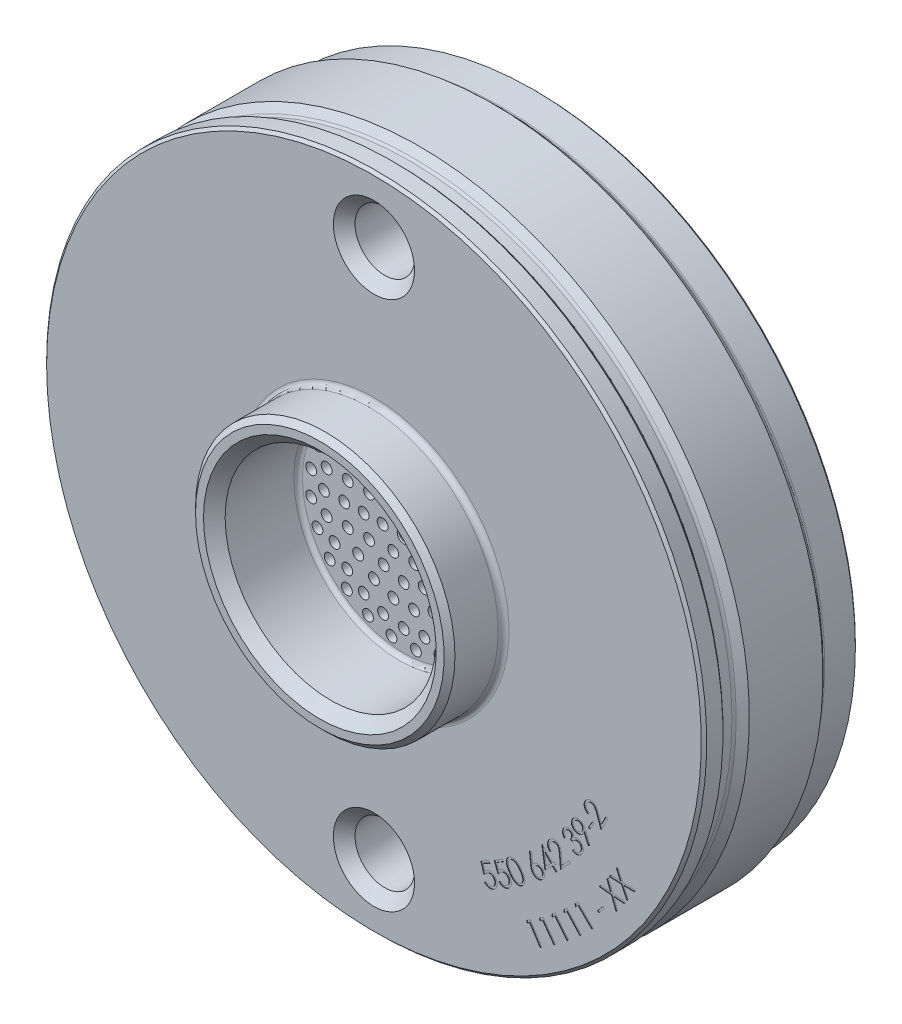
SolidWorks part; units mm, degrees
material "4140 H-T"
ref_plane "Front Plane" through (0, 0, 0) normal (0, 0, 1) x (1, 0, 0)
ref_plane "Top Plane" through (0, 0, 0) normal (0, 1, 0) x (1, 0, 0)
ref_plane "Right Plane" through (0, 0, 0) normal (1, 0, 0) x (0, 0, -1)
sketch "Sketch1" plane through (0, 0, 0) normal (1, 0, 0) x (0, 0, -1)
  line L0 (0, 48.5) -> (0, 59)
  line L1 (-0.5, 59.5) -> (-6.1686, 59.5)
  line L2 (-23.3314, 59.5) -> (-25.18, 59.5)
  line L3 (-39.98, 21.5) -> (-37.98, 19.5)
  line L4 (-6.7343, 59.7343) -> (-7.95, 60.95)
  line L5 (-7.95, 60.95) -> (-21.55, 60.95)
  line L6 (-21.55, 60.95) -> (-22.7657, 59.7343)
  line L7 (-37.98, 19.5) -> (-24.48, 19.5)
  line L8 (-24.48, 0) -> (-18.95, 0)
  line L11 (-24.48, 19.5) -> (-24.48, 0)
  line L12 (-25.98, 60.3) -> (-25.98, 60.5)
  line L13 (-26.48, 61) -> (-29.48, 61)
  line L14 (-29.98, 60.5) -> (-29.98, 24.975)
  line L15 (-30.98, 23.975) -> (-38.98, 23.975)
  line L20 (-38.98, 23.975) -> (-39.98, 22.975)
  line L21 (-39.98, 22.975) -> (-39.98, 21.5)
  line L26 (0, 0) -> (-52.2303, 0) construction
  line L27 (-18.95, 0) -> (-18.95, 24.2431)
  line L30 (-29.48, 61) -> (-29.98, 60.5)
  line L31 (-25.98, 60.5) -> (-26.48, 61)
  line L32 (0, 59) -> (-0.5, 59.5)
  arc A0 (-18.95, 24.2431) -> (-2.274, 45.5892) centre (3.05, 24.2431) cw
  arc A1 (-30.98, 23.975) -> (-29.98, 24.975) centre (-30.98, 24.975) ccw
  arc A3 (-23.3314, 59.5) -> (-22.7657, 59.7343) centre (-23.3314, 60.3) ccw
  arc A4 (-25.98, 60.3) -> (-25.18, 59.5) centre (-25.18, 60.3) ccw
  arc A5 (-6.7343, 59.7343) -> (-6.1686, 59.5) centre (-6.1686, 60.3) ccw
  arc A6 (0, 48.5) -> (-2.274, 45.5892) centre (-3, 48.5) cw
  point P1 (0, 59.5)
  point P9 (-23, 59.5)
  point P14 (-25.98, 61)
  point P15 (-29.98, 61)
  point P44 (-6.5, 59.5)
  dimension "D31" = 0.8
  dimension "D32" = 3
  dimension "D34" = 29.98
  dimension "D9" = 22
  dimension "D11" = 1
  dimension "D1" = 121.9
  dimension "D6" = 45
  dimension "D7" = 122
  dimension "D8" = 18.95
  dimension "D10" = 10
  dimension "D12" = 47.95
  dimension "D13" = 43
  dimension "D14" = 39
  dimension "D15" = 15.5
  dimension "D16" = 45
  dimension "D18" = 1
  dimension "D21" = 119
  dimension "D22" = 45
  dimension "D26" = 6.5
  dimension "D27" = 23
  dimension "D29" = 45
  dimension "D30" = 4
  dimension "D33" = 97
revolve "Revolve1" add sketch "Sketch1" angle 360 about L26
cosmetic thread "Cosmetic Thread1" parameters "D1"=21.1314, "D2"=119.6
sketch "Sketch15" plane through (0, 0, 29.98) normal (0, 0, 1) x (1, 0, 0)
  line L0 (0, 0) -> (70.0011, 0) construction
  circle A0 centre (0, 0) radius 49 construction
  point P4 (49, 0)
  point P8 (0, -49)
  point P9 (-49, 0)
  point P10 (0, 49)
  dimension "D1" = 98
  dimension "D2" = 4
hole_wizard "Ø11.0 (11) Diameter Hole1" positions "Sketch17" profile "Sketch16" hole size "Ø11.0" standard "Ansi Metric"
sketch "Sketch17" plane through (0, 0, 29.98) normal (0, 0, 1) x (1, 0, 0)
  point P2 (0, -49)
  point P6 (0, 49)
sketch "Sketch16" plane through (0, -49, 29.98) normal (1, 0, 0) x (0, -1, 0)
  line L0 (0, 0) -> (0, 15.3047)
  line L1 (0, 15.3047) -> (5.5, 12)
  line L2 (5.5, 12) -> (5.5, 2)
  line L3 (5.5, 2) -> (7.5, 0)
  line L5 (7.5, 0) -> (0, 0)
  line L6 (-5.5, 2) -> (-7.5, 0) construction
  line L10 (0, 15.3047) -> (-5.5, 12) construction
  line L11 (0, -6.35) -> (0, 107.95) construction
  dimension "Hole Dia." = 11
  dimension "Hole Depth" = 12
  dimension "Near C'Sink Dia." = 15
  dimension "Near C'Sink Angle" = 90
  dimension "Drill Angle" = 118
sketch "Sketch19" plane through (0, 0, 39.98) normal (0, 0, 1) x (1, 0, 0)
  circle A0 centre (0, 0) radius 13.5 construction
  point P3 (0, 13.5)
  dimension "D1" = 27
sketch "Sketch18" plane through (0, 0, 29.98) normal (0, 0, 1) x (1, 0, 0)
  line L0 (0, 0) -> (-74.7152, 0) construction
  line L1 (0, 0) -> (0, -71.1316) construction
  line L2 (0, 0) -> (82.8113, 0) construction
  line L3 (0, 0) -> (-45.0534, -31.5467) construction
  arc A0 (0, -48) -> (48, 0) centre (0, 0) ccw construction
  arc A1 (-55, 0) -> (-45.0534, -31.5467) centre (0, 0) ccw construction
  text T0 "550 642 39-2\r\n11111 - XX" font "Century Gothic" height 4
  dimension "D1" = 48
  dimension "D2" = 55
  dimension "D3" = 35
extrude "Cut-Extrude1" cut sketch "Sketch18" against normal blind 0.1
sketch "Sketch27" plane through (0, 0, 24.48) normal (0, 0, 1) x (1, 0, 0)
  line L0 (0, 0) -> (36.2899, 0) construction
  line L1 (1.95, 3.3775) -> (0, 0) construction
  line L2 (0, 0) -> (17.1024, 2.2516) construction
  circle A0 centre (0, 0) radius 3.9 construction
  circle A2 centre (0, 0) radius 7.4 construction
  circle A3 centre (0, 0) radius 11 construction
  circle A4 centre (0, 0) radius 14.75 construction
  circle A5 centre (0, 0) radius 17.25 construction
  point P4 (3.9, 0)
  point P5 (1.95, -3.3775)
  point P6 (-1.95, -3.3775)
  point P7 (-3.9, 0)
  point P9 (7.4, 0)
  point P10 (-1.95, 3.3775)
  point P11 (1.95, 3.3775)
  point P12 (0, 0)
  point P13 (6.4086, -3.7)
  point P15 (11, 0)
  point P16 (10.3366, -3.7622)
  point P17 (3.7, -6.4086)
  point P18 (0, -7.4)
  point P19 (-3.7, -6.4086)
  point P20 (-6.4086, -3.7)
  point P21 (-7.4, 0)
  point P22 (-6.4086, 3.7)
  point P23 (-3.7, 6.4086)
  point P24 (0, 7.4)
  point P25 (3.7, 6.4086)
  point P26 (6.4086, 3.7)
  point P27 (0, 0)
  point P29 (14.75, 0)
  point P31 (8.4265, -7.0707)
  point P32 (5.5, -9.5263)
  point P33 (1.9101, -10.8329)
  point P34 (-1.9101, -10.8329)
  point P35 (-5.5, -9.5263)
  point P36 (-8.4265, -7.0707)
  point P37 (-10.3366, -3.7622)
  point P38 (-11, 0)
  point P39 (-10.3366, 3.7622)
  point P40 (-8.4265, 7.0707)
  point P41 (-5.5, 9.5263)
  point P42 (-1.9101, 10.8329)
  point P43 (1.9101, 10.8329)
  point P44 (5.5, 9.5263)
  point P45 (8.4265, 7.0707)
  point P46 (10.3366, 3.7622)
  point P47 (0, 0)
  point P50 (14.2474, -3.8176)
  point P51 (12.7739, -7.375)
  point P52 (10.4298, -10.4298)
  point P53 (7.375, -12.7739)
  point P54 (3.8176, -14.2474)
  point P55 (0, -14.75)
  point P56 (-3.8176, -14.2474)
  point P57 (-7.375, -12.7739)
  point P58 (-10.4298, -10.4298)
  point P59 (-12.7739, -7.375)
  point P60 (-14.2474, -3.8176)
  point P61 (-14.75, 0)
  point P62 (-14.2474, 3.8176)
  point P63 (-12.7739, 7.375)
  point P64 (-10.4298, 10.4298)
  point P65 (-7.375, 12.7739)
  point P66 (-3.8176, 14.2474)
  point P67 (0, 14.75)
  point P68 (3.8176, 14.2474)
  point P69 (7.375, 12.7739)
  point P70 (10.4298, 10.4298)
  point P71 (12.7739, 7.375)
  point P72 (14.2474, 3.8176)
  point P73 (0, 0)
  point P74 (17.1024, -2.2516)
  point P75 (17.1024, 2.2516)
  point P78 (15.9369, -6.6013)
  point P79 (13.6853, -10.5011)
  point P80 (10.5011, -13.6853)
  point P81 (6.6013, -15.9369)
  point P82 (2.2516, -17.1024)
  point P83 (-2.2516, -17.1024)
  point P84 (-6.6013, -15.9369)
  point P85 (-10.5011, -13.6853)
  point P86 (-13.6853, -10.5011)
  point P87 (-15.9369, -6.6013)
  point P88 (-17.1024, -2.2516)
  point P89 (-17.1024, 2.2516)
  point P90 (-15.9369, 6.6013)
  point P91 (-13.6853, 10.5011)
  point P92 (-10.5011, 13.6853)
  point P93 (-6.6013, 15.9369)
  point P94 (-2.2516, 17.1024)
  point P95 (2.2516, 17.1024)
  point P96 (6.6013, 15.9369)
  point P97 (10.5011, 13.6853)
  point P98 (13.6853, 10.5011)
  point P99 (15.9369, 6.6013)
  point P100 (0, 0)
  dimension "D1" = 7.8
  dimension "D2" = 6
  dimension "D3" = 14.8
  dimension "D5" = 22
  dimension "D7" = 29.5
  dimension "D9" = 34.5
  dimension "D10" = 7.5
  dimension "D4" = 12
  dimension "D6" = 18
  dimension "D8" = 24
  dimension "D11" = 24
hole_wizard "Ø2.0 (2) Diameter Hole1" positions "Sketch26" profile "Sketch25" hole size "Ø2.0" standard "ANSI Metric" end condition up to next
sketch "Sketch26" plane through (0, 0, 24.48) normal (0, 0, 1) x (1, 0, 0)
  point P265 (1.95, 3.3775)
  point P268 (-1.95, 3.3775)
  point P271 (-3.9, 0)
  point P274 (-1.95, -3.3775)
  point P277 (1.95, -3.3775)
  point P280 (3.9, 0)
  point P283 (6.4086, 3.7)
  point P286 (3.7, 6.4086)
  point P289 (0, 7.4)
  point P292 (-3.7, 6.4086)
  point P295 (-6.4086, 3.7)
  point P298 (-7.4, 0)
  point P301 (-6.4086, -3.7)
  point P304 (-3.7, -6.4086)
  point P307 (0, -7.4)
  point P310 (3.7, -6.4086)
  point P313 (6.4086, -3.7)
  point P316 (7.4, 0)
  point P319 (10.3366, 3.7622)
  point P322 (8.4265, 7.0707)
  point P325 (5.5, 9.5263)
  point P328 (1.9101, 10.8329)
  point P331 (-1.9101, 10.8329)
  point P334 (-5.5, 9.5263)
  point P337 (-8.4265, 7.0707)
  point P340 (-10.3366, 3.7622)
  point P343 (-11, 0)
  point P346 (-10.3366, -3.7622)
  point P349 (-8.4265, -7.0707)
  point P352 (-10.4298, -10.4298)
  point P355 (-5.5, -9.5263)
  point P358 (-7.375, -12.7739)
  point P361 (-3.8176, -14.2474)
  point P364 (-1.9101, -10.8329)
  point P367 (0, -14.75)
  point P370 (1.9101, -10.8329)
  point P373 (3.8176, -14.2474)
  point P376 (7.375, -12.7739)
  point P379 (5.5, -9.5263)
  point P382 (8.4265, -7.0707)
  point P385 (10.4298, -10.4298)
  point P388 (12.7739, -7.375)
  point P391 (10.3366, -3.7622)
  point P394 (11, 0)
  point P397 (14.75, 0)
  point P400 (14.2474, -3.8176)
  point P403 (14.2474, 3.8176)
  point P406 (12.7739, 7.375)
  point P409 (-12.7739, -7.375)
  point P412 (-14.2474, -3.8176)
  point P415 (-15.9369, -6.6013)
  point P418 (-13.6853, -10.5011)
  point P421 (-10.5011, -13.6853)
  point P424 (-6.6013, -15.9369)
  point P427 (-2.2516, -17.1024)
  point P430 (2.2516, -17.1024)
  point P433 (6.6013, -15.9369)
  point P436 (10.5011, -13.6853)
  point P439 (13.6853, -10.5011)
  point P442 (15.9369, -6.6013)
  point P445 (17.1024, -2.2516)
  point P448 (17.1024, 2.2516)
  point P451 (-14.75, 0)
  point P454 (-14.2474, 3.8176)
  point P457 (-17.1024, 2.2516)
  point P460 (-17.1024, -2.2516)
  point P463 (-15.9369, 6.6013)
  point P466 (-12.7739, 7.375)
  point P469 (-13.6853, 10.5011)
  point P472 (-10.4298, 10.4298)
  point P475 (-10.5011, 13.6853)
  point P478 (-7.375, 12.7739)
  point P481 (-6.6013, 15.9369)
  point P484 (-3.8176, 14.2474)
  point P487 (-2.2516, 17.1024)
  point P490 (0, 14.75)
  point P493 (2.2516, 17.1024)
  point P496 (3.8176, 14.2474)
  point P499 (6.6013, 15.9369)
  point P502 (7.375, 12.7739)
  point P505 (10.5011, 13.6853)
  point P508 (10.4298, 10.4298)
  point P511 (13.6853, 10.5011)
  point P514 (15.9369, 6.6013)
  point P517 (0, 0)
sketch "Sketch25" plane through (1.95, 3.3775, 24.48) normal (1, 0, 0) x (0, -1, 0)
  line L0 (0, 0) -> (0, 5.53)
  line L1 (0, 5.53) -> (1, 5.53)
  line L2 (1, 5.53) -> (1, 0)
  line L5 (1, 0) -> (0, 0)
  line L11 (0, -6.35) -> (0, 107.95) construction
  dimension "Thru Hole Dia." = 2
  dimension "Thru Hole Depth" = 5.53
fillet "Fillet1" radius 0.8 1 edges at (-19.5, 0, 24.48)
chamfer "Chamfer1" distance 0.2 angle 45 1 edges at (1, 0, 24.48)
